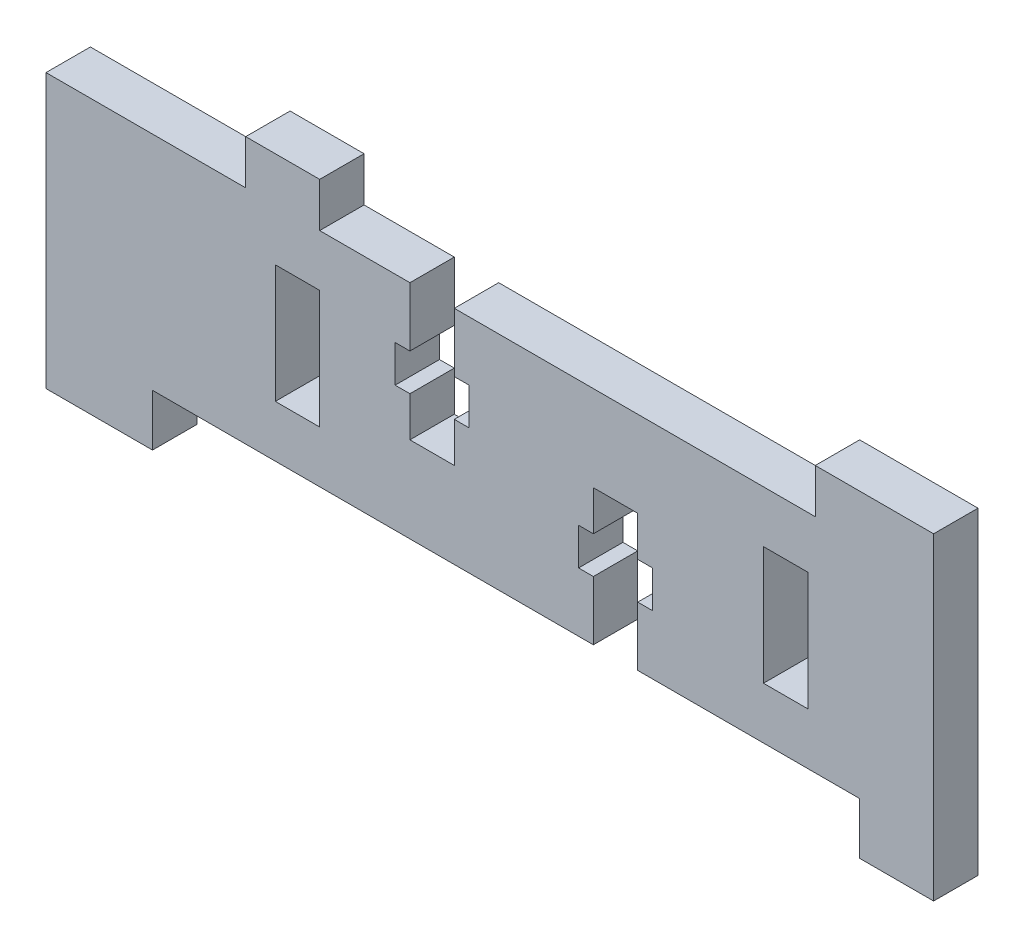
SolidWorks part; units mm, degrees
material "Balsa"
ref_plane "Front Plane" through (0, 0, 0) normal (0, 0, 1) x (1, 0, 0)
ref_plane "Top Plane" through (0, 0, 0) normal (0, 1, 0) x (1, 0, 0)
ref_plane "Right Plane" through (0, 0, 0) normal (1, 0, 0) x (0, 0, -1)
sketch "Sketch1" plane through (0, 0, 0) normal (0, 0, 1) x (1, 0, 0)
  line L0 (30.4, -9) -> (30.4, -5.5)
  line L1 (-11.1, 12.5) -> (-6.1, 12.5)
  line L2 (-24.6, 9.5) -> (-24.6, -9)
  line L3 (-24.6, -9) -> (-17.4, -9)
  line L4 (35.4, 12.5) -> (35.4, -9)
  line L5 (-24.6, -5.5) -> (-24.6, 9.5)
  line L6 (23.9, 6) -> (23.9, 9.5) construction
  line L7 (30.4, -5.5) -> (15.4, -5.5)
  line L8 (15.4, -5.5) -> (15.4, -1.5)
  line L9 (15.4, -1.5) -> (16.4, -1.5)
  line L10 (16.4, -1.5) -> (16.4, 1)
  line L11 (16.4, 1) -> (15.4, 1)
  line L12 (15.4, 1) -> (15.4, 3.7)
  line L13 (15.4, 3.7) -> (12.4, 3.7)
  line L14 (12.4, 3.7) -> (12.4, 1)
  line L15 (12.4, 1) -> (11.4, 1)
  line L16 (11.4, 1) -> (11.4, -1.5)
  line L17 (11.4, -1.5) -> (12.4, -1.5)
  line L18 (12.4, -1.5) -> (12.4, -5.5)
  line L19 (12.4, -5.5) -> (-17.4, -5.5)
  line L20 (-17.4, -5.5) -> (-17.4, -9)
  line L21 (30.4, -9) -> (35.4, -9)
  line L22 (35.4, 12.5) -> (27.4, 12.5)
  line L23 (27.4, 12.5) -> (27.4, 9.5)
  line L24 (27.4, 9.5) -> (3, 9.5)
  line L25 (3, 9.5) -> (3, 5.5)
  line L26 (3, 5.5) -> (4, 5.5)
  line L27 (4, 5.5) -> (4, 3)
  line L28 (4, 3) -> (3, 3)
  line L29 (3, 3) -> (3, 0.3)
  line L30 (3, 0.3) -> (0, 0.3)
  line L31 (0, 0.3) -> (0, 3)
  line L32 (0, 3) -> (-1, 3)
  line L33 (-1, 3) -> (-1, 5.5)
  line L34 (-1, 5.5) -> (0, 5.5)
  line L35 (0, 5.5) -> (0, 9.5)
  line L36 (0, 9.5) -> (-6.1, 9.5)
  line L37 (-6.1, 9.5) -> (-6.1, 12.5)
  line L38 (-6.1, 12.5) -> (-11.1, 12.5)
  line L39 (-11.1, 12.5) -> (-11.1, 9.5)
  line L40 (-11.1, 9.5) -> (-24.6, 9.5)
  line L42 (27.4, 12.5) -> (35.4, 12.5)
  line L43 (23.9, 6) -> (26.9, 6)
  line L44 (23.9, 6) -> (23.9, -2)
  line L45 (23.9, -2) -> (26.9, -2)
  line L46 (26.9, 6) -> (26.9, -2)
  line L47 (-9.1, -2) -> (-6.1, -2)
  line L48 (-9.1, -2) -> (-9.1, 6)
  line L49 (-9.1, 6) -> (-6.1, 6)
  line L50 (-6.1, -2) -> (-6.1, 6)
  line L51 (23.9, -2) -> (23.9, -5.5) construction
  line L52 (3, 9.5) -> (0, 9.5) construction
  line L53 (12.4, -5.5) -> (15.4, -5.5) construction
  line L54 (27.4, 9.5) -> (35.4, 9.5) construction
  line L55 (-11.1, 9.5) -> (-6.1, 9.5) construction
  line L56 (30.4, -9) -> (-17.4, -9) construction
  line L57 (-17.4, -5.5) -> (-24.6, -5.5) construction
  line L58 (27.4, 12.5) -> (-6.1, 12.5) construction
  line L59 (-17.4, -9) -> (30.4, -9) construction
  line L62 (-6.1, 6) -> (-6.1, 9.5) construction
  line L63 (-6.1, -2) -> (-6.1, -5.5) construction
  point P0 (0, 0)
  point P47 (-1, 4.25)
  dimension "D29" = 8
  dimension "D2" = 3.5
  dimension "D3" = 4
  dimension "D4" = 2.5
  dimension "D5" = 9.2
  dimension "D6" = 3
  dimension "D7" = 1
  dimension "D8" = 5
  dimension "D9" = 20
  dimension "D10" = 5
  dimension "D11" = 7.2
  dimension "D14" = 5
  dimension "D15" = 8
  dimension "D16" = 4
  dimension "D17" = 2.5
  dimension "D19" = 5
  dimension "D20" = 1
  dimension "D21" = 3
  dimension "D22" = 33.5
  dimension "D23" = 32.4
  dimension "D24" = 3
  dimension "D26" = 60
  dimension "D30" = 3
  dimension "D31" = 8.5
  dimension "D32" = 30
  dimension "D33" = 15
extrude "Boss-Extrude1" add sketch "Sketch1" along normal mid plane 3
